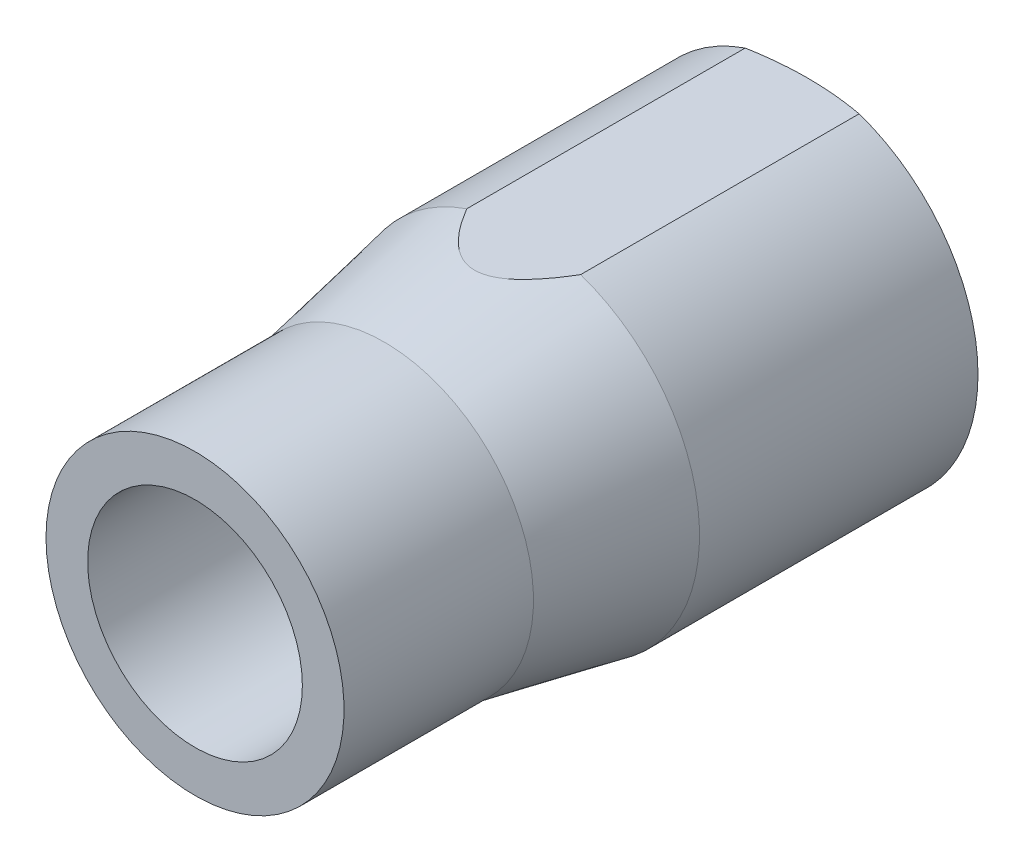
SolidWorks part; units mm, degrees
ref_plane "Front" through (0, 0, 0) normal (0, 0, 1) x (1, 0, 0)
ref_plane "Top" through (0, 0, 0) normal (0, 1, 0) x (1, 0, 0)
ref_plane "Right" through (0, 0, 0) normal (1, 0, 0) x (0, 0, -1)
sketch "Sketch1" plane through (0, 0, 0) normal (0, 0, 1) x (1, 0, 0)
  circle A0 centre (0, 0) radius 5.2451
  dimension "D1" = 10.4902
extrude "Boss-Extrude1" add sketch "Sketch1" along normal blind 9.7155
chamfer "Chamfer1" distance 2.54 angle 29 1 edges at (5.2451, 0, 0)
ref_plane "Plane1" through (0, 0, 13.8684) normal (0, 0, 1) x (1, 0, 0)
sketch "Sketch2" plane through (0, 0, 13.8684) normal (0, 0, 1) x (1, 0, 0)
  circle A0 centre (0, 0) radius 4.445
  dimension "D1" = 8.89
loft "Loft1" add profiles "Sketch2" section edge at (5.2451, 0, 9.7155) section "Sketch2"
sketch "Sketch3" plane through (0, 0, 13.8684) normal (0, 0, 1) x (1, 0, 0)
  circle A1 centre (0, 0) radius 4.445
  dimension "D1" = 8.89
extrude "Boss-Extrude2" add sketch "Sketch3" along normal blind 5.6515
sketch "Sketch4" plane through (0, 0, 0) normal (0, 0, -1) x (-1, 0, 0)
  circle A0 centre (0, 0) radius 2.0699
  dimension "D1" = 4.1397
extrude "Cut-Extrude1" cut sketch "Sketch4" against normal blind 13.7795
sketch "Sketch5" plane through (0, 0, 0) normal (0, 0, 1) x (1, 0, 0)
  line L0 (0, 0) -> (-6.219, 0) construction
  line L1 (-7.7883, 4.9621) -> (7.3814, 4.9621)
  line L2 (-7.7883, 4.9621) -> (-7.7883, -4.9621)
  line L3 (-7.7883, -4.9621) -> (7.3814, -4.9621)
  line L4 (7.3814, 4.9621) -> (7.3814, -4.9621)
  dimension "D1" = 9.9242
  dimension "D2" = 15.1697
extrude "Cut-Extrude2" cut sketch "Sketch5" along normal blind 11.7475 flip side to cut
sketch "Sketch6" plane through (0, 0, 19.5199) normal (0, 0, 1) x (1, 0, 0)
  circle A0 centre (0, 0) radius 3.2024
  dimension "D1" = 6.4049
extrude "Cut-Extrude3" cut sketch "Sketch6" against normal blind 8.1915
